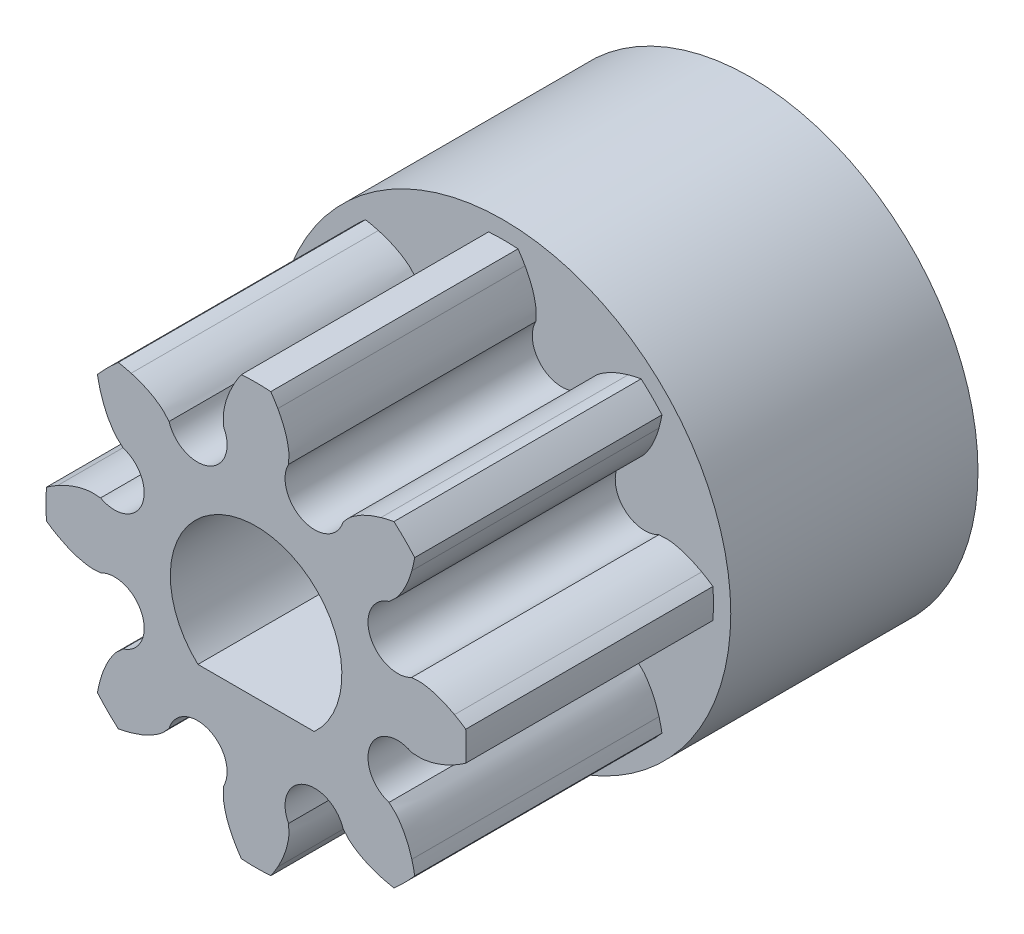
SolidWorks part; units mm, degrees
ref_plane "Front Plane" through (0, 0, 0) normal (0, 0, 1) x (1, 0, 0)
ref_plane "Top Plane" through (0, 0, 0) normal (0, 1, 0) x (1, 0, 0)
ref_plane "Right Plane" through (0, 0, 0) normal (1, 0, 0) x (0, 0, -1)
sketch "Sketch2" plane through (0, 0, 0) normal (0, 0, 1) x (1, 0, 0)
  arc A20 (398.7038, 134.7054) -> (399.2275, 135.2291) centre (395.233, 138.6999) ccw
  arc A21 (395.6033, 143.9786) -> (394.8627, 143.9786) centre (395.233, 138.6999) ccw
  arc A22 (391.2386, 135.2291) -> (391.7623, 134.7054) centre (395.233, 138.6999) ccw
  arc A23 (389.9543, 139.0702) -> (389.9543, 138.3296) centre (395.233, 138.6999) ccw
  arc A24 (391.7623, 142.6943) -> (391.2386, 142.1706) centre (395.233, 138.6999) ccw
  arc A25 (394.8627, 133.4212) -> (395.6033, 133.4212) centre (395.233, 138.6999) ccw
  arc A26 (400.5117, 138.3296) -> (400.5117, 139.0702) centre (395.233, 138.6999) ccw
  arc A27 (399.2275, 142.1706) -> (398.7038, 142.6943) centre (395.233, 138.6999) ccw
  arc A28 (389.9543, 138.3296) -> (391.2775, 135.1848) centre (395.233, 138.6999) ccw
  arc A29 (391.7623, 134.7054) -> (394.9008, 133.4186) centre (395.233, 138.6999) ccw
  arc A30 (395.0573, 133.4111) -> (398.7358, 142.6663) centre (395.233, 138.6999) ccw
  arc A31 (398.7038, 142.6943) -> (395.5653, 143.9811) centre (395.233, 138.6999) ccw
  arc A32 (395.1155, 143.9902) -> (395.0573, 143.9886) centre (395.233, 138.6999) ccw
  arc A33 (394.8805, 143.9798) -> (391.7623, 142.6943) centre (395.233, 138.6999) ccw
  arc A34 (391.2386, 142.1706) -> (389.9543, 139.0702) centre (395.233, 138.6999) ccw
  arc A35 (391.0811, 137.8736) -> (391.7133, 136.3478) centre (395.233, 138.6999) ccw
  arc A36 (392.8814, 135.1798) -> (394.4073, 134.5479) centre (395.233, 138.6999) ccw
  arc A37 (396.0592, 134.5479) -> (397.585, 135.18) centre (395.233, 138.6999) ccw
  arc A38 (398.753, 136.3481) -> (399.385, 137.8741) centre (395.233, 138.6999) ccw
  arc A39 (399.3849, 139.5261) -> (398.7528, 141.052) centre (395.233, 138.6999) ccw
  arc A40 (397.5846, 142.22) -> (396.0588, 142.8519) centre (395.233, 138.6999) ccw
  arc A41 (394.4068, 142.8518) -> (392.8811, 142.2197) centre (395.233, 138.6999) ccw
  arc A42 (391.713, 141.0516) -> (391.081, 139.5257) centre (395.233, 138.6999) ccw
  arc A43 (391.2178, 137.8779) -> (391.8127, 136.4418) centre (395.233, 138.6999) ccw
  arc A44 (392.9751, 135.2794) -> (394.411, 134.6846) centre (395.233, 138.6999) ccw
  arc A45 (396.055, 134.6847) -> (397.491, 135.2794) centre (395.233, 138.6999) ccw
  arc A46 (398.6534, 136.4419) -> (399.2483, 137.8779) centre (395.233, 138.6999) ccw
  arc A47 (399.2482, 139.5218) -> (398.6534, 140.9579) centre (395.233, 138.6999) ccw
  arc A48 (397.491, 142.1203) -> (396.055, 142.7151) centre (395.233, 138.6999) ccw
  arc A49 (394.411, 142.7151) -> (392.9751, 142.1203) centre (395.233, 138.6999) ccw
  arc A50 (391.8126, 140.9579) -> (391.2178, 139.5218) centre (395.233, 138.6999) ccw
  arc A51 (392.2686, 137.5629) -> (392.3332, 137.407) centre (395.233, 138.6999) ccw
  arc A52 (393.941, 135.7997) -> (394.0961, 135.7354) centre (395.233, 138.6999) ccw
  arc A53 (396.3699, 135.7354) -> (396.5251, 135.7997) centre (395.233, 138.6999) ccw
  arc A54 (398.1329, 137.407) -> (398.1975, 137.563) centre (395.233, 138.6999) ccw
  arc A55 (398.1975, 139.8368) -> (398.1329, 139.9927) centre (395.233, 138.6999) ccw
  arc A56 (396.5251, 141.6001) -> (396.3699, 141.6643) centre (395.233, 138.6999) ccw
  arc A57 (394.0961, 141.6643) -> (393.9409, 141.6001) centre (395.233, 138.6999) ccw
  arc A58 (392.3332, 139.9927) -> (392.2685, 139.8368) centre (395.233, 138.6999) ccw
  circle A59 centre (395.233, 138.6999) radius 1.7066
  circle A60 centre (395.233, 138.6999) radius 1.5875
  spline S32 degree 3 poles (396.4238, 141.5746) (396.4013, 141.6097) (396.3557, 141.6842) (396.2913, 141.8005) (396.2311, 141.9232) (396.1768, 142.0488) (396.13, 142.1772) (396.0921, 142.3087) (396.065, 142.4426) (396.0459, 142.5785) (396.0549, 142.7151) (396.0639, 142.8517) (396.0447, 142.9876) (396.0176, 143.1215) (395.9797, 143.253) (395.9329, 143.3815) (395.8787, 143.507) (395.8272, 143.6119) (395.7934, 143.6746) (395.7809, 143.697) knots 0 0 0 0 0.055614 0.116309 0.177003 0.237696 0.298386 0.359073 0.419758 0.480433 0.541052 0.601671 0.662346 0.723031 0.783718 0.844407 0.905101 0.965795 1 1 1 1
  spline S33 degree 3 poles (398.3791, 142.6208) (398.3544, 142.6137) (398.2862, 142.5933) (398.1756, 142.5556) (398.0485, 142.5052) (397.9246, 142.4474) (397.8048, 142.3813) (397.691, 142.3057) (397.5813, 142.2232) (397.4911, 142.1202) (397.4009, 142.0173) (397.2912, 141.9347) (397.1774, 141.8592) (397.0576, 141.793) (396.9337, 141.7353) (396.8066, 141.6849) (396.6772, 141.6407) (396.5494, 141.6039) (396.4645, 141.5835) (396.4238, 141.5746) knots 0 0 0 0 0.034205 0.094899 0.155593 0.216282 0.276969 0.337654 0.398329 0.458948 0.519567 0.580242 0.640927 0.701614 0.762304 0.822997 0.883691 0.944386 1 1 1 1
  spline S34 degree 3 poles (398.1077, 139.8906) (398.1167, 139.9314) (398.1371, 140.0163) (398.1738, 140.144) (398.218, 140.2734) (398.2684, 140.4005) (398.3262, 140.5245) (398.3923, 140.6442) (398.4679, 140.7581) (398.5504, 140.8677) (398.6534, 140.9579) (398.7563, 141.0482) (398.8389, 141.1578) (398.9144, 141.2716) (398.9806, 141.3914) (399.0383, 141.5154) (399.0887, 141.6425) (399.1265, 141.753) (399.1469, 141.8213) (399.1539, 141.846) knots 0 0 0 0 0.055614 0.116309 0.177003 0.237696 0.298386 0.359073 0.419758 0.480433 0.541052 0.601671 0.662346 0.723031 0.783718 0.844407 0.905101 0.965795 1 1 1 1
  spline S35 degree 3 poles (400.2302, 139.2477) (400.2077, 139.2602) (400.145, 139.294) (400.0401, 139.3455) (399.9146, 139.3998) (399.7862, 139.4466) (399.6547, 139.4845) (399.5208, 139.5116) (399.3849, 139.5307) (399.2483, 139.5217) (399.1117, 139.5127) (398.9758, 139.5319) (398.8419, 139.559) (398.7104, 139.5969) (398.5819, 139.6437) (398.4564, 139.6979) (398.3337, 139.7582) (398.2174, 139.8225) (398.1429, 139.8681) (398.1077, 139.8906) knots 0 0 0 0 0.034205 0.094899 0.155593 0.216282 0.276969 0.337654 0.398329 0.458948 0.519567 0.580242 0.640927 0.701614 0.762304 0.822997 0.883691 0.944386 1 1 1 1
  spline S36 degree 3 poles (398.1077, 137.5091) (398.1429, 137.5316) (398.2174, 137.5772) (398.3337, 137.6416) (398.4564, 137.7018) (398.5819, 137.7561) (398.7104, 137.8029) (398.8419, 137.8408) (398.9758, 137.8679) (399.1117, 137.887) (399.2483, 137.878) (399.3849, 137.869) (399.5208, 137.8882) (399.6547, 137.9152) (399.7862, 137.9531) (399.9146, 138) (400.0401, 138.0542) (400.145, 138.1057) (400.2077, 138.1395) (400.2302, 138.152) knots 0 0 0 0 0.055614 0.116309 0.177003 0.237696 0.298386 0.359073 0.419758 0.480433 0.541052 0.601671 0.662346 0.723031 0.783718 0.844407 0.905101 0.965795 1 1 1 1
  spline S37 degree 3 poles (399.1539, 135.5538) (399.1469, 135.5784) (399.1265, 135.6467) (399.0887, 135.7573) (399.0383, 135.8844) (398.9806, 136.0083) (398.9144, 136.1281) (398.8389, 136.2419) (398.7563, 136.3516) (398.6534, 136.4418) (398.5504, 136.532) (398.4679, 136.6417) (398.3923, 136.7555) (398.3262, 136.8753) (398.2684, 136.9992) (398.218, 137.1263) (398.1738, 137.2557) (398.1371, 137.3835) (398.1167, 137.4684) (398.1077, 137.5091) knots 0 0 0 0 0.034205 0.094899 0.155593 0.216282 0.276969 0.337654 0.398329 0.458948 0.519567 0.580242 0.640927 0.701614 0.762304 0.822997 0.883691 0.944386 1 1 1 1
  spline S38 degree 3 poles (396.4238, 135.8252) (396.4645, 135.8162) (396.5494, 135.7958) (396.6772, 135.7591) (396.8066, 135.7149) (396.9337, 135.6645) (397.0576, 135.6067) (397.1774, 135.5406) (397.2912, 135.465) (397.4009, 135.3825) (397.4911, 135.2795) (397.5813, 135.1766) (397.691, 135.094) (397.8048, 135.0185) (397.9246, 134.9523) (398.0485, 134.8946) (398.1756, 134.8442) (398.2862, 134.8064) (398.3544, 134.786) (398.3791, 134.779) knots 0 0 0 0 0.055614 0.116309 0.177003 0.237696 0.298386 0.359073 0.419758 0.480433 0.541052 0.601671 0.662346 0.723031 0.783718 0.844407 0.905101 0.965795 1 1 1 1
  spline S39 degree 3 poles (395.7809, 133.7027) (395.7934, 133.7252) (395.8272, 133.7879) (395.8787, 133.8927) (395.9329, 134.0183) (395.9797, 134.1467) (396.0176, 134.2782) (396.0447, 134.4121) (396.0639, 134.548) (396.0549, 134.6846) (396.0459, 134.8212) (396.065, 134.9571) (396.0921, 135.091) (396.13, 135.2225) (396.1768, 135.351) (396.2311, 135.4765) (396.2913, 135.5992) (396.3557, 135.7155) (396.4013, 135.79) (396.4238, 135.8252) knots 0 0 0 0 0.034205 0.094899 0.155593 0.216282 0.276969 0.337654 0.398329 0.458948 0.519567 0.580242 0.640927 0.701614 0.762304 0.822997 0.883691 0.944386 1 1 1 1
  spline S40 degree 3 poles (394.0423, 135.8252) (394.0648, 135.79) (394.1104, 135.7155) (394.1747, 135.5992) (394.235, 135.4765) (394.2892, 135.351) (394.336, 135.2225) (394.3739, 135.091) (394.401, 134.9571) (394.4202, 134.8212) (394.4112, 134.6846) (394.4022, 134.548) (394.4213, 134.4121) (394.4484, 134.2782) (394.4863, 134.1467) (394.5331, 134.0183) (394.5874, 133.8927) (394.6388, 133.7879) (394.6727, 133.7252) (394.6852, 133.7027) knots 0 0 0 0 0.055614 0.116309 0.177003 0.237696 0.298386 0.359073 0.419758 0.480433 0.541052 0.601671 0.662346 0.723031 0.783718 0.844407 0.905101 0.965795 1 1 1 1
  spline S41 degree 3 poles (392.0869, 134.779) (392.1116, 134.786) (392.1799, 134.8064) (392.2904, 134.8442) (392.4175, 134.8946) (392.5415, 134.9523) (392.6613, 135.0185) (392.7751, 135.094) (392.8847, 135.1766) (392.975, 135.2795) (393.0652, 135.3825) (393.1748, 135.465) (393.2887, 135.5406) (393.4084, 135.6067) (393.5324, 135.6645) (393.6595, 135.7149) (393.7889, 135.7591) (393.9166, 135.7958) (394.0015, 135.8162) (394.0423, 135.8252) knots 0 0 0 0 0.034205 0.094899 0.155593 0.216282 0.276969 0.337654 0.398329 0.458948 0.519567 0.580242 0.640927 0.701614 0.762304 0.822997 0.883691 0.944386 1 1 1 1
  spline S42 degree 3 poles (392.3583, 137.5091) (392.3494, 137.4684) (392.3289, 137.3835) (392.2922, 137.2557) (392.248, 137.1263) (392.1976, 136.9992) (392.1399, 136.8753) (392.0737, 136.7555) (391.9982, 136.6417) (391.9156, 136.532) (391.8127, 136.4418) (391.7097, 136.3516) (391.6272, 136.2419) (391.5516, 136.1281) (391.4855, 136.0083) (391.4277, 135.8844) (391.3773, 135.7573) (391.3396, 135.6467) (391.3191, 135.5784) (391.3121, 135.5538) knots 0 0 0 0 0.055614 0.116309 0.177003 0.237696 0.298386 0.359073 0.419758 0.480433 0.541052 0.601671 0.662346 0.723031 0.783718 0.844407 0.905101 0.965795 1 1 1 1
  spline S43 degree 3 poles (390.2359, 138.152) (390.2583, 138.1395) (390.321, 138.1057) (390.4259, 138.0542) (390.5514, 138) (390.6799, 137.9531) (390.8114, 137.9152) (390.9453, 137.8882) (391.0812, 137.869) (391.2178, 137.878) (391.3544, 137.887) (391.4903, 137.8679) (391.6242, 137.8408) (391.7557, 137.8029) (391.8841, 137.7561) (392.0097, 137.7018) (392.1324, 137.6416) (392.2487, 137.5772) (392.3232, 137.5316) (392.3583, 137.5091) knots 0 0 0 0 0.034205 0.094899 0.155593 0.216282 0.276969 0.337654 0.398329 0.458948 0.519567 0.580242 0.640927 0.701614 0.762304 0.822997 0.883691 0.944386 1 1 1 1
  spline S44 degree 3 poles (392.3583, 139.8906) (392.3232, 139.8681) (392.2487, 139.8225) (392.1324, 139.7582) (392.0097, 139.6979) (391.8841, 139.6437) (391.7557, 139.5969) (391.6242, 139.559) (391.4903, 139.5319) (391.3544, 139.5127) (391.2178, 139.5217) (391.0812, 139.5307) (390.9453, 139.5116) (390.8114, 139.4845) (390.6799, 139.4466) (390.5514, 139.3998) (390.4259, 139.3455) (390.321, 139.294) (390.2583, 139.2602) (390.2359, 139.2477) knots 0 0 0 0 0.055614 0.116309 0.177003 0.237696 0.298386 0.359073 0.419758 0.480433 0.541052 0.601671 0.662346 0.723031 0.783718 0.844407 0.905101 0.965795 1 1 1 1
  spline S45 degree 3 poles (391.3121, 141.846) (391.3191, 141.8213) (391.3396, 141.753) (391.3773, 141.6425) (391.4277, 141.5154) (391.4855, 141.3914) (391.5516, 141.2716) (391.6272, 141.1578) (391.7097, 141.0482) (391.8127, 140.9579) (391.9156, 140.8677) (391.9982, 140.7581) (392.0737, 140.6442) (392.1399, 140.5245) (392.1976, 140.4005) (392.248, 140.2734) (392.2922, 140.144) (392.3289, 140.0163) (392.3494, 139.9314) (392.3583, 139.8906) knots 0 0 0 0 0.034205 0.094899 0.155593 0.216282 0.276969 0.337654 0.398329 0.458948 0.519567 0.580242 0.640927 0.701614 0.762304 0.822997 0.883691 0.944386 1 1 1 1
  spline S46 degree 3 poles (394.0423, 141.5746) (394.0015, 141.5835) (393.9166, 141.6039) (393.7889, 141.6407) (393.6595, 141.6849) (393.5324, 141.7353) (393.4084, 141.793) (393.2887, 141.8592) (393.1748, 141.9347) (393.0652, 142.0173) (392.975, 142.1202) (392.8847, 142.2232) (392.7751, 142.3057) (392.6613, 142.3813) (392.5415, 142.4474) (392.4175, 142.5052) (392.2904, 142.5556) (392.1799, 142.5933) (392.1116, 142.6137) (392.0869, 142.6208) knots 0 0 0 0 0.055614 0.116309 0.177003 0.237696 0.298386 0.359073 0.419758 0.480433 0.541052 0.601671 0.662346 0.723031 0.783718 0.844407 0.905101 0.965795 1 1 1 1
  spline S47 degree 3 poles (394.6852, 143.697) (394.6727, 143.6746) (394.6388, 143.6119) (394.5874, 143.507) (394.5331, 143.3815) (394.4863, 143.253) (394.4484, 143.1215) (394.4213, 142.9876) (394.4022, 142.8517) (394.4112, 142.7151) (394.4202, 142.5785) (394.401, 142.4426) (394.3739, 142.3087) (394.336, 142.1772) (394.2892, 142.0488) (394.235, 141.9232) (394.1747, 141.8005) (394.1104, 141.6842) (394.0648, 141.6097) (394.0423, 141.5746) knots 0 0 0 0 0.034205 0.094899 0.155593 0.216282 0.276969 0.337654 0.398329 0.458948 0.519567 0.580242 0.640927 0.701614 0.762304 0.822997 0.883691 0.944386 1 1 1 1
  spline S48 degree 3 poles (394.6852, 143.697) (394.6948, 143.7144) (394.7273, 143.7712) (394.7854, 143.8658) (394.8365, 143.9413) (394.8627, 143.9786) knots 0 0 0 0 0.179128 0.589562 1 1 1 1
  spline S49 degree 3 poles (395.6033, 143.9786) (395.6296, 143.9413) (395.6806, 143.8658) (395.7388, 143.7712) (395.7712, 143.7144) (395.7809, 143.697) knots 0 0 0 0 0.410438 0.820872 1 1 1 1
  spline S50 degree 3 poles (398.3791, 142.6208) (398.3983, 142.6262) (398.4614, 142.6435) (398.5694, 142.6693) (398.6589, 142.6866) (398.7038, 142.6943) knots 0 0 0 0 0.179128 0.589562 1 1 1 1
  spline S51 degree 3 poles (399.2275, 142.1706) (399.2197, 142.1257) (399.2024, 142.0362) (399.1767, 141.9282) (399.1594, 141.8651) (399.1539, 141.846) knots 0 0 0 0 0.410438 0.820872 1 1 1 1
  spline S52 degree 3 poles (400.2302, 139.2477) (400.2475, 139.2381) (400.3044, 139.2056) (400.399, 139.1475) (400.4745, 139.0964) (400.5117, 139.0702) knots 0 0 0 0 0.179128 0.589562 1 1 1 1
  spline S53 degree 3 poles (400.5117, 138.3296) (400.4745, 138.3033) (400.399, 138.2523) (400.3044, 138.1941) (400.2475, 138.1617) (400.2302, 138.152) knots 0 0 0 0 0.410438 0.820872 1 1 1 1
  spline S54 degree 3 poles (399.1539, 135.5538) (399.1594, 135.5346) (399.1767, 135.4715) (399.2024, 135.3635) (399.2197, 135.274) (399.2275, 135.2291) knots 0 0 0 0 0.179128 0.589562 1 1 1 1
  spline S55 degree 3 poles (391.7623, 142.6943) (391.8072, 142.6866) (391.8966, 142.6693) (392.0047, 142.6435) (392.0678, 142.6262) (392.0869, 142.6208) knots 0 0 0 0 0.410438 0.820872 1 1 1 1
  spline S56 degree 3 poles (391.3121, 141.846) (391.3067, 141.8651) (391.2894, 141.9282) (391.2636, 142.0362) (391.2463, 142.1257) (391.2386, 142.1706) knots 0 0 0 0 0.179128 0.589562 1 1 1 1
  spline S57 degree 3 poles (398.7038, 134.7054) (398.6589, 134.7132) (398.5694, 134.7305) (398.4614, 134.7562) (398.3983, 134.7735) (398.3791, 134.779) knots 0 0 0 0 0.410438 0.820872 1 1 1 1
  spline S58 degree 3 poles (389.9543, 139.0702) (389.9915, 139.0964) (390.0671, 139.1475) (390.1617, 139.2056) (390.2185, 139.2381) (390.2359, 139.2477) knots 0 0 0 0 0.410438 0.820872 1 1 1 1
  spline S59 degree 3 poles (390.2359, 138.152) (390.2185, 138.1617) (390.1617, 138.1941) (390.0671, 138.2523) (389.9915, 138.3033) (389.9543, 138.3296) knots 0 0 0 0 0.179128 0.589562 1 1 1 1
  spline S60 degree 3 poles (391.2386, 135.2291) (391.2463, 135.274) (391.2636, 135.3635) (391.2894, 135.4715) (391.3067, 135.5346) (391.3121, 135.5538) knots 0 0 0 0 0.410438 0.820872 1 1 1 1
  spline S61 degree 3 poles (395.7809, 133.7027) (395.7712, 133.6854) (395.7388, 133.6285) (395.6806, 133.5339) (395.6296, 133.4584) (395.6033, 133.4212) knots 0 0 0 0 0.179128 0.589562 1 1 1 1
  spline S62 degree 3 poles (392.0869, 134.779) (392.0678, 134.7735) (392.0047, 134.7562) (391.8966, 134.7305) (391.8072, 134.7132) (391.7623, 134.7054) knots 0 0 0 0 0.179128 0.589562 1 1 1 1
  spline S63 degree 3 poles (394.8627, 133.4212) (394.8365, 133.4584) (394.7854, 133.5339) (394.7273, 133.6285) (394.6948, 133.6854) (394.6852, 133.7027) knots 0 0 0 0 0.410438 0.820872 1 1 1 1
sketch "Sketch3" plane through (0, 0, 0) normal (0, 0, 1) x (1, 0, 0)
  line L0 (395.233, 138.6999) -> (395.233, 143.9915)
  arc A0 (395.6033, 143.9786) -> (394.8627, 143.9786) centre (395.233, 138.6999) ccw construction
  spline S0 degree 3 poles (2372.952, -154.1091) (298.7524, 115.4314) (388.2149, 156.01) (402.1514, 133.3401) (342.9629, 84.3959) (-1603.2057, 179.888) knots -128.386463 -128.386463 -128.386463 -128.386463 0.410438 0.820872 111.276784 111.276784 111.276784 111.276784 only from (395.6033, 143.9786) to (395.7809, 143.697) construction
  spline S1 degree 3 poles (-1580.9376, 439.5213) (499.9701, 169.1411) (403.2826, 129.1669) (396.2913, 141.8005) (396.2311, 141.9232) (396.1768, 142.0488) (396.13, 142.1772) (396.0921, 142.3087) (396.065, 142.4426) (396.0459, 142.5785) (396.0549, 142.7151) (396.0639, 142.8517) (396.0447, 142.9876) (396.0176, 143.1215) (395.9797, 143.253) (395.9329, 143.3815) (395.8787, 143.507) (390.049, 155.3839) (301.1286, 123.8906) (2370.04, -174.6802) knots -19.051928 -19.051928 -19.051928 -19.051928 0.055614 0.116309 0.177003 0.237696 0.298386 0.359073 0.419758 0.480433 0.541052 0.601671 0.662346 0.723031 0.783718 0.844407 0.905101 0.965795 18.464194 18.464194 18.464194 18.464194 only from (396.4238, 141.5746) to (395.7809, 143.697) construction
  spline S2 degree 3 poles (-1222.8113, 1313.4485) (451.3037, 61.6852) (410.6962, 146.8316) (398.1756, 142.5556) (398.0485, 142.5052) (397.9246, 142.4474) (397.8048, 142.3813) (397.691, 142.3057) (397.5813, 142.2232) (397.4911, 142.1202) (397.4009, 142.0173) (397.2912, 141.9347) (397.1774, 141.8592) (397.0576, 141.793) (396.9337, 141.7353) (396.8066, 141.6849) (396.6772, 141.6407) (382.8002, 137.651) (342.6977, 234.286) (2005.3389, -1045.9594) knots -17.464307 -17.464307 -17.464307 -17.464307 0.034205 0.094899 0.155593 0.216282 0.276969 0.337654 0.398329 0.458948 0.519567 0.580242 0.640927 0.701614 0.762304 0.822997 0.883691 0.944386 20.051987 20.051987 20.051987 20.051987 only from (398.3791, 142.6208) to (396.4238, 141.5746) construction
  spline S3 degree 3 poles (1837.4528, -1245.3531) (393.7949, 63.3404) (386.551, 139.802) (412.4357, 145.9774) (447.0021, 54.0237) (-1210.2827, 1330.1297) knots -110.276933 -110.276933 -110.276933 -110.276933 0.179128 0.589562 129.386974 129.386974 129.386974 129.386974 only from (398.3791, 142.6208) to (398.7038, 142.6943) construction
  spline S4 degree 3 poles (395.6033, 143.9786) (395.6296, 143.9413) (395.6806, 143.8658) (395.7388, 143.7712) (395.7712, 143.7144) (395.7809, 143.697) knots 0 0 0 0 0.410438 0.820872 1 1 1 1
  spline S5 degree 3 poles (396.4238, 141.5746) (396.4013, 141.6097) (396.3557, 141.6842) (396.2913, 141.8005) (396.2311, 141.9232) (396.1768, 142.0488) (396.13, 142.1772) (396.0921, 142.3087) (396.065, 142.4426) (396.0459, 142.5785) (396.0549, 142.7151) (396.0639, 142.8517) (396.0447, 142.9876) (396.0176, 143.1215) (395.9797, 143.253) (395.9329, 143.3815) (395.8787, 143.507) (395.8272, 143.6119) (395.7934, 143.6746) (395.7809, 143.697) knots 0 0 0 0 0.055614 0.116309 0.177003 0.237696 0.298386 0.359073 0.419758 0.480433 0.541052 0.601671 0.662346 0.723031 0.783718 0.844407 0.905101 0.965795 1 1 1 1
  spline S6 degree 3 poles (398.3791, 142.6208) (398.3544, 142.6137) (398.2862, 142.5933) (398.1756, 142.5556) (398.0485, 142.5052) (397.9246, 142.4474) (397.8048, 142.3813) (397.691, 142.3057) (397.5813, 142.2232) (397.4911, 142.1202) (397.4009, 142.0173) (397.2912, 141.9347) (397.1774, 141.8592) (397.0576, 141.793) (396.9337, 141.7353) (396.8066, 141.6849) (396.6772, 141.6407) (396.5494, 141.6039) (396.4645, 141.5835) (396.4238, 141.5746) knots 0 0 0 0 0.034205 0.094899 0.155593 0.216282 0.276969 0.337654 0.398329 0.458948 0.519567 0.580242 0.640927 0.701614 0.762304 0.822997 0.883691 0.944386 1 1 1 1
  spline S7 degree 3 poles (398.3791, 142.6208) (398.3983, 142.6262) (398.4614, 142.6435) (398.5694, 142.6693) (398.6589, 142.6866) (398.7038, 142.6943) knots 0 0 0 0 0.179128 0.589562 1 1 1 1
sketch "Sketch4" plane through (0, 0, 0) normal (0, 0, 1) x (1, 0, 0)
  line L1 (395.233, 138.6999) -> (395.233, 144.0974)
  spline S4 degree 3 poles (395.6107, 144.0841) (395.6375, 144.0462) (395.6896, 143.9691) (395.7489, 143.8727) (395.782, 143.8147) (395.7918, 143.797) knots 0 0 0 0 0.410438 0.820872 1 1 1 1
  spline S5 degree 3 poles (396.4476, 141.6321) (396.4246, 141.6679) (396.3781, 141.7439) (396.3125, 141.8625) (396.251, 141.9877) (396.1957, 142.1157) (396.1479, 142.2468) (396.1093, 142.3809) (396.0817, 142.5175) (396.0621, 142.6561) (396.0713, 142.7954) (396.0805, 142.9348) (396.061, 143.0734) (396.0333, 143.2099) (395.9947, 143.3441) (395.9469, 143.4751) (395.8916, 143.6031) (395.8391, 143.7101) (395.8046, 143.7741) (395.7918, 143.797) knots 0 0 0 0 0.055614 0.116309 0.177003 0.237696 0.298386 0.359073 0.419758 0.480433 0.541052 0.601671 0.662346 0.723031 0.783718 0.844407 0.905101 0.965795 1 1 1 1
  spline S6 degree 3 poles (398.4421, 142.6992) (398.4169, 142.692) (398.3472, 142.6712) (398.2345, 142.6327) (398.1048, 142.5813) (397.9784, 142.5224) (397.8562, 142.4549) (397.7401, 142.3778) (397.6283, 142.2936) (397.5363, 142.1886) (397.4442, 142.0836) (397.3324, 141.9994) (397.2163, 141.9224) (397.0941, 141.8549) (396.9677, 141.796) (396.838, 141.7446) (396.7061, 141.6995) (396.5758, 141.662) (396.4892, 141.6412) (396.4476, 141.6321) knots 0 0 0 0 0.034205 0.094899 0.155593 0.216282 0.276969 0.337654 0.398329 0.458948 0.519567 0.580242 0.640927 0.701614 0.762304 0.822997 0.883691 0.944386 1 1 1 1
  spline S7 degree 3 poles (398.4421, 142.6992) (398.4616, 142.7047) (398.526, 142.7224) (398.6361, 142.7486) (398.7274, 142.7663) (398.7732, 142.7742) knots 0 0 0 0 0.179128 0.589562 1 1 1 1
sketch "Sketch7" plane through (0, 0, 0) normal (0, 0, 1) x (1, 0, 0)
  circle A0 centre (395.233, 138.6999) radius 5.3975
extrude "Boss-Extrude2" add sketch "Sketch7" along normal blind 6.35
sketch "Sketch8" plane through (0, 0, 6.35) normal (0, 0, 1) x (1, 0, 0)
  line L0 (395.233, 138.6999) -> (396.4476, 141.6321)
  arc A0 (396.0665, 142.694) -> (397.468, 142.1135) centre (396.7392, 142.336) ccw
  spline S0 degree 3 poles (396.4476, 141.6321) (396.4246, 141.6679) (396.3781, 141.7439) (396.3125, 141.8625) (396.251, 141.9877) (396.1957, 142.1157) (396.1479, 142.2468) (396.1093, 142.3809) (396.0817, 142.5175) (396.0621, 142.6561) (396.0713, 142.7954) (396.0805, 142.9348) (396.061, 143.0734) (396.0333, 143.2099) (395.9947, 143.3441) (395.9469, 143.4751) (395.8916, 143.6031) (395.8391, 143.7101) (395.8046, 143.7741) (395.7918, 143.797) knots 0 0 0 0 0.055614 0.116309 0.177003 0.237696 0.298386 0.359073 0.419758 0.480433 0.541052 0.601671 0.662346 0.723031 0.783718 0.844407 0.905101 0.965795 1 1 1 1 construction
  spline S1 degree 3 poles (398.4421, 142.6992) (398.4169, 142.692) (398.3472, 142.6712) (398.2345, 142.6327) (398.1048, 142.5813) (397.9784, 142.5224) (397.8562, 142.4549) (397.7401, 142.3778) (397.6283, 142.2936) (397.5363, 142.1886) (397.4442, 142.0836) (397.3324, 141.9994) (397.2163, 141.9224) (397.0941, 141.8549) (396.9677, 141.796) (396.838, 141.7446) (396.7061, 141.6995) (396.5758, 141.662) (396.4892, 141.6412) (396.4476, 141.6321) knots 0 0 0 0 0.034205 0.094899 0.155593 0.216282 0.276969 0.337654 0.398329 0.458948 0.519567 0.580242 0.640927 0.701614 0.762304 0.822997 0.883691 0.944386 1 1 1 1 construction
  point P4 (396.0665, 142.694)
  point P5 (397.468, 142.1135)
  dimension "D1" = 0.762
sketch "Sketch9" plane through (0, 0, 6.35) normal (0, 0, 1) x (1, 0, 0)
  arc A0 (396.0665, 142.694) -> (397.468, 142.1135) centre (396.7392, 142.336) ccw construction
  circle A1 centre (395.233, 138.6999) radius 5.3975
  circle A2 centre (395.233, 138.6999) radius 5.3975
  arc A3 (396.0665, 142.694) -> (397.468, 142.1135) centre (396.7392, 142.336) ccw
  arc A4 (395.6107, 144.0841) -> (398.7732, 142.7742) centre (396.5446, 141.8664) cw
  spline S0 degree 3 poles (2372.8549, -154.8063) (297.9635, 115.4828) (388.1226, 156.278) (402.2455, 133.305) (342.728, 83.9807) (-1603.1659, 178.7559) knots -127.576539 -127.576539 -127.576539 -127.576539 0.410438 0.820872 110.529833 110.529833 110.529833 110.529833 only from (395.6107, 144.0841) to (395.7918, 143.797) construction
  spline S1 degree 3 poles (-1580.8088, 440.3793) (500.8359, 169.2425) (403.3992, 129.0565) (396.3125, 141.8625) (396.251, 141.9877) (396.1957, 142.1157) (396.1479, 142.2468) (396.1093, 142.3809) (396.0817, 142.5175) (396.0621, 142.6561) (396.0713, 142.7954) (396.0805, 142.9348) (396.061, 143.0734) (396.0333, 143.2099) (395.9947, 143.3441) (395.9469, 143.4751) (395.8916, 143.6031) (389.9824, 155.642) (300.3792, 123.9951) (2370.0088, -175.2382) knots -18.932157 -18.932157 -18.932157 -18.932157 0.055614 0.116309 0.177003 0.237696 0.298386 0.359073 0.419758 0.480433 0.541052 0.601671 0.662346 0.723031 0.783718 0.844407 0.905101 0.965795 18.354222 18.354222 18.354222 18.354222 only from (396.4476, 141.6321) to (395.7918, 143.797) construction
  spline S2 degree 3 poles (-1223.157, 1313.0117) (451.907, 61.2301) (410.9257, 146.967) (398.2345, 142.6327) (398.1048, 142.5813) (397.9784, 142.5224) (397.8562, 142.4549) (397.7401, 142.3778) (397.6283, 142.2936) (397.5363, 142.1886) (397.4442, 142.0836) (397.3324, 141.9994) (397.2163, 141.9224) (397.0941, 141.8549) (396.9677, 141.796) (396.838, 141.7446) (396.7061, 141.6995) (382.6399, 137.6554) (342.1579, 234.9681) (2005.8069, -1045.225) knots -17.354241 -17.354241 -17.354241 -17.354241 0.034205 0.094899 0.155593 0.216282 0.276969 0.337654 0.398329 0.458948 0.519567 0.580242 0.640927 0.701614 0.762304 0.822997 0.883691 0.944386 19.932036 19.932036 19.932036 19.932036 only from (398.4421, 142.6992) to (396.4476, 141.6321) construction
  spline S3 degree 3 poles (1836.6758, -1246.1723) (393.6676, 62.8789) (386.4595, 139.8436) (412.6904, 146.1017) (447.5956, 53.5042) (-1210.6551, 1329.528) knots -109.53129 -109.53129 -109.53129 -109.53129 0.179128 0.589562 128.57571 128.57571 128.57571 128.57571 only from (398.4421, 142.6992) to (398.7732, 142.7742) construction
  spline S4 degree 3 poles (395.6107, 144.0841) (395.6375, 144.0462) (395.6896, 143.9691) (395.7489, 143.8727) (395.782, 143.8147) (395.7918, 143.797) knots 0 0 0 0 0.410438 0.820872 1 1 1 1
  spline S5 degree 3 poles (396.0665, 142.694) (396.0669, 142.7278) (396.0721, 142.808) (396.0805, 142.9348) (396.061, 143.0734) (396.0333, 143.2099) (395.9947, 143.3441) (395.9469, 143.4751) (395.8916, 143.6031) (395.8391, 143.7101) (395.8046, 143.7741) (395.7918, 143.797) knots 0.496893 0.496893 0.496893 0.496893 0.541052 0.601671 0.662346 0.723031 0.783718 0.844407 0.905101 0.965795 1 1 1 1
  spline S6 degree 3 poles (398.4421, 142.6992) (398.4169, 142.692) (398.3472, 142.6712) (398.2345, 142.6327) (398.1048, 142.5813) (397.9784, 142.5224) (397.8562, 142.4549) (397.7401, 142.3778) (397.6283, 142.2936) (397.5446, 142.1981) (397.4916, 142.1376) (397.468, 142.1135) knots 0 0 0 0 0.034205 0.094899 0.155593 0.216282 0.276969 0.337654 0.398329 0.458948 0.503107 0.503107 0.503107 0.503107
  spline S7 degree 3 poles (398.4421, 142.6992) (398.4616, 142.7047) (398.526, 142.7224) (398.6361, 142.7486) (398.7274, 142.7663) (398.7732, 142.7742) knots 0 0 0 0 0.179128 0.589562 1 1 1 1
  dimension "D1" = 0
extrude "Cut-Extrude2" cut sketch "Sketch9" against normal blind 7.62 contours A4 S7 S6 A3 S5 S4
ref_axis "Axis2" through (395.233, 138.6999, 6.35) along (0, 0, -1)
pattern_circular "CirPattern2" count 8 over 360 about axis through (395.233, 138.6999, 6.35) along (0, 0, -1) of "Cut-Extrude2"
sketch "Sketch10" plane through (0, 0, 0) normal (0, 0, -1) x (-1, 0, 0)
  circle A0 centre (-395.233, 138.6999) radius 5.842
  dimension "D1" = 11.684
extrude "Boss-Extrude3" add sketch "Sketch10" along normal blind 6.35
sketch "Sketch11" plane through (0, 0, -6.35) normal (0, 0, -1) x (-1, 0, 0)
  line L0 (-396.6451, 137.2836) -> (-393.8209, 137.2836) construction
  line L1 (-396.7268, 137.0804) -> (-393.7393, 137.0804)
  arc A0 (-393.8209, 137.2836) -> (-396.6451, 137.2836) centre (-395.233, 138.6999) ccw construction
  arc A1 (-393.7393, 137.0804) -> (-396.7268, 137.0804) centre (-395.233, 138.6999) ccw
  point P1 (-395.233, 140.6999)
  dimension "D1" = 4
  dimension "D2" = 3.4163
  dimension "D3" = 0.2032
extrude "Cut-Extrude3" cut sketch "Sketch11" against normal through all
